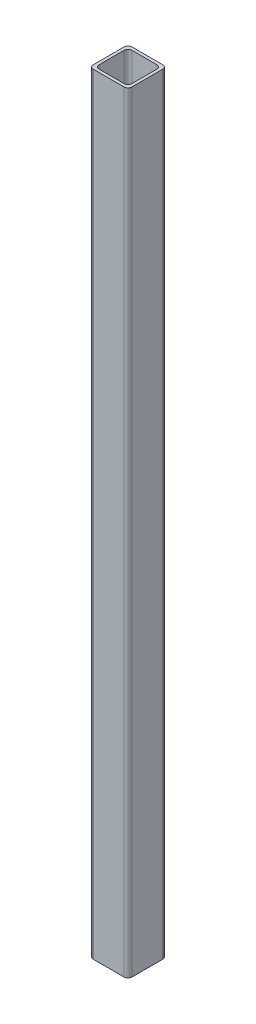
SolidWorks part; units mm, degrees
material "Hexcel AS4C (3000 Filaments)"
ref_plane "Front Plane" through (0, 0, 0) normal (0, 0, 1) x (1, 0, 0)
ref_plane "Top Plane" through (0, 0, 0) normal (0, 1, 0) x (1, 0, 0)
ref_plane "Right Plane" through (0, 0, 0) normal (1, 0, 0) x (0, 0, -1)
sketch "Sketch1" plane through (0, 0, 0) normal (0, 1, 0) x (1, 0, 0)
  line L1 (-4, -5) -> (4, -5)
  line L2 (-5, -4) -> (-5, 4)
  line L3 (-4, 5) -> (4, 5)
  line L4 (5, -4) -> (5, 4)
  line L5 (-5, -5) -> (5, 5) construction
  line L6 (-5, 5) -> (5, -5) construction
  line L7 (-3.25, -4.25) -> (3.25, -4.25)
  line L8 (-4.25, -3.25) -> (-4.25, 3.25)
  line L9 (-3.25, 4.25) -> (3.25, 4.25)
  line L10 (4.25, -3.25) -> (4.25, 3.25)
  line L11 (-4.25, -4.25) -> (4.25, 4.25) construction
  line L12 (-4.25, 4.25) -> (4.25, -4.25) construction
  arc A0 (-4, -5) -> (-5, -4) centre (-4, -4) cw
  arc A1 (4, 5) -> (5, 4) centre (4, 4) cw
  arc A2 (4, -5) -> (5, -4) centre (4, -4) ccw
  arc A3 (-5, 4) -> (-4, 5) centre (-4, 4) cw
  arc A4 (-3.25, -4.25) -> (-4.25, -3.25) centre (-3.25, -3.25) cw
  arc A5 (3.25, -4.25) -> (4.25, -3.25) centre (3.25, -3.25) ccw
  arc A6 (3.25, 4.25) -> (4.25, 3.25) centre (3.25, 3.25) cw
  arc A7 (-4.25, 3.25) -> (-3.25, 4.25) centre (-3.25, 3.25) cw
  point P0 (0, 0)
  point P18 (0, 0)
  dimension "D3" = 1
  dimension "D6" = 1
  dimension "D7" = 1
  dimension "D8" = 1
  dimension "D9" = 1
  dimension "D1" = 10
  dimension "D2" = 10
  dimension "D4" = 8.5
  dimension "D5" = 8.5
extrude "Boss-Extrude1" add sketch "Sketch1" along normal blind 200
